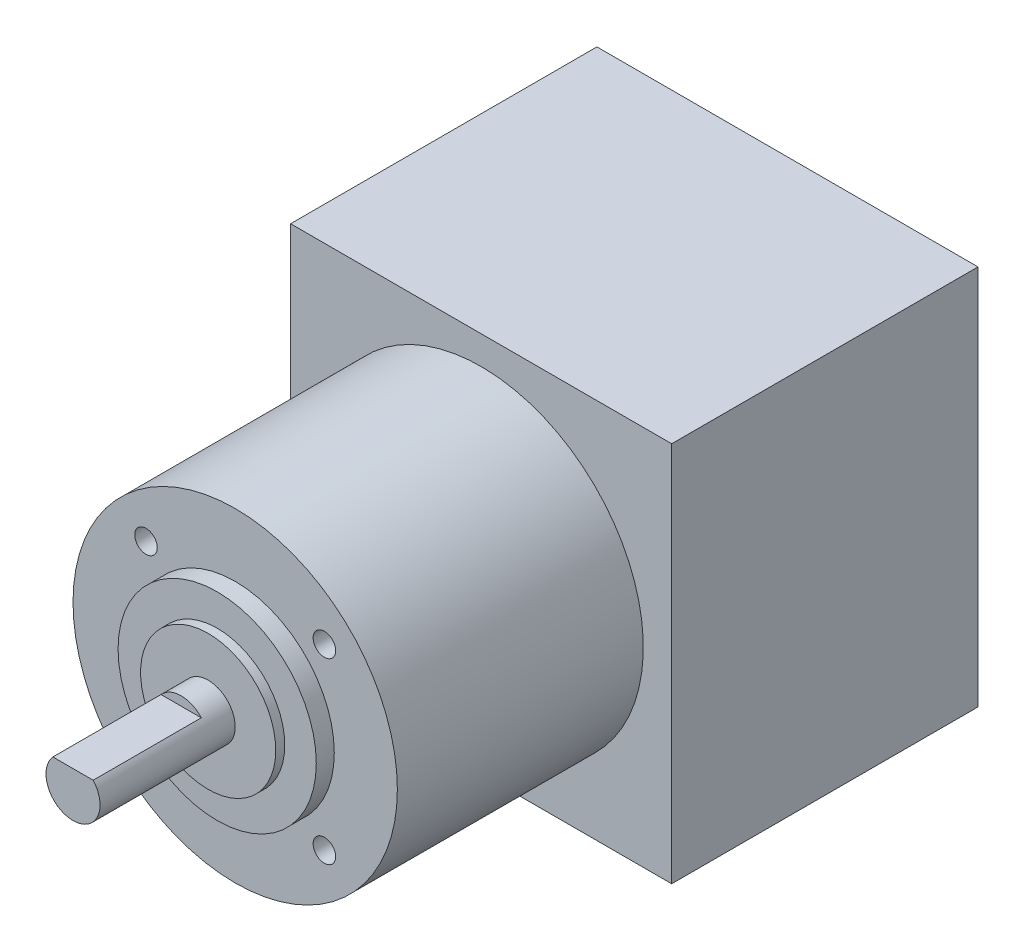
SolidWorks part; units mm, degrees
ref_plane "Ebene vorne" through (0, 0, 0) normal (0, 0, 1) x (1, 0, 0)
ref_plane "Ebene oben" through (0, 0, 0) normal (0, 1, 0) x (1, 0, 0)
ref_plane "Ebene rechts" through (0, 0, 0) normal (1, 0, 0) x (0, 0, -1)
sketch "Skizze1" plane through (0, 0, 0) normal (0, 0, 1) x (1, 0, 0)
  line L1 (0, 0) -> (42.3, 0)
  line L2 (0, 0) -> (0, 42.3)
  line L3 (0, 42.3) -> (42.3, 42.3)
  line L4 (42.3, 0) -> (42.3, 42.3)
  dimension "D1" = 42.3
extrude "Aufsatz-Linear austragen1" add sketch "Skizze1" along normal blind 34
sketch "Skizze2" plane through (0, 0, 34) normal (0, 0, 1) x (1, 0, 0)
  line L0 (0, 42.3) -> (42.3, 0) construction
  circle A0 centre (21.15, 21.15) radius 18
  dimension "D1" = 36
extrude "Aufsatz-Linear austragen2" add sketch "Skizze2" along normal blind 27.3
sketch "Skizze3" plane through (0, 0, 61.3) normal (0, 0, 1) x (1, 0, 0)
  circle A0 centre (21.15, 21.15) radius 11
  dimension "D1" = 22
extrude "Aufsatz-Linear austragen3" add sketch "Skizze3" along normal blind 2
sketch "Skizze4" plane through (0, 0, 63.3) normal (0, 0, 1) x (1, 0, 0)
  circle A0 centre (21.15, 21.15) radius 7.5
  dimension "D1" = 15
extrude "Aufsatz-Linear austragen4" add sketch "Skizze4" along normal blind 1
sketch "Skizze5" plane through (0, 0, 64.3) normal (0, 0, 1) x (1, 0, 0)
  circle A0 centre (21.15, 21.15) radius 3
  dimension "D1" = 6
extrude "Aufsatz-Linear austragen5" add sketch "Skizze5" along normal blind 15
sketch "Skizze6" plane through (0, 0, 79.3) normal (0, 0, 1) x (1, 0, 0)
  line L0 (23.3861, 23.15) -> (18.9139, 23.15)
  circle A0 centre (21.15, 21.15) radius 3 construction
  arc A1 (23.3861, 23.15) -> (18.9139, 23.15) centre (21.15, 21.15) ccw
  dimension "D1" = 2
extrude "Schnitt-Linear austragen1" cut sketch "Skizze6" against normal blind 12
hole_wizard "M3 Gewindebohrung1" positions "Skizze8" profile "Skizze7" tap size "M3" standard "ISO"
sketch "Skizze8" plane through (0, 0, 61.3) normal (0, 0, 1) x (1, 0, 0)
  line L1 (11.2505, 31.0495) -> (31.0495, 31.0495) construction
  line L2 (11.2505, 31.0495) -> (11.2505, 11.2505) construction
  line L3 (11.2505, 11.2505) -> (31.0495, 11.2505) construction
  line L4 (31.0495, 31.0495) -> (31.0495, 11.2505) construction
  line L5 (31.0495, 31.0495) -> (11.2505, 11.2505) construction
  line L9 (0, 42.3) -> (42.3, 0) construction
  line L11 (0, 0) -> (42.3, 42.3) construction
  point P0 (11.2505, 11.2505)
  point P2 (31.0495, 11.2505)
  point P4 (31.0495, 31.0495)
  point P6 (11.2505, 31.0495)
  dimension "D1" = 28
sketch "Skizze7" plane through (11.2505, 11.2505, 61.3) normal (1, 0, 0) x (0, -1, 0)
  line L0 (0, 0) -> (0, 9.2511)
  line L1 (0, 9.2511) -> (1.25, 8.5)
  line L2 (1.25, 8.5) -> (1.25, 0)
  line L5 (1.25, 0) -> (0, 0)
  line L10 (0, 9.2511) -> (-1.25, 8.5) construction
  line L11 (0, -6.35) -> (0, 107.95) construction
  dimension "Bohrerdurchmesser" = 2.5
  dimension "Bohrungstiefe" = 8.5
  dimension "Spitzenwinkel" = 118
cosmetic thread "Bohrungsgewinde1" parameters "D1"=6, "D2"=3
cosmetic thread "Bohrungsgewinde2" parameters "D1"=6, "D2"=3
cosmetic thread "Bohrungsgewinde3" parameters "D1"=6, "D2"=3
cosmetic thread "Bohrungsgewinde4" parameters "D1"=6, "D2"=3
sketch "Skizze9" plane through (0, 0, 0) normal (0, -1, 0) x (-1, 0, 0)
  line L0 (-21.15, -10) -> (0, -10) construction
  line L1 (0, -34) -> (0, 0) construction
  line L2 (-21.15, -10) -> (-42.3, -10) construction
  line L3 (-42.3, -34) -> (-42.3, 0) construction
  line L4 (0, 0) -> (-42.3, 0) construction
  circle A0 centre (-21.15, -10) radius 5.5
  dimension "D1" = 11
  dimension "D2" = 10
extrude "Aufsatz-Linear austragen6" add sketch "Skizze9" along normal blind 5
